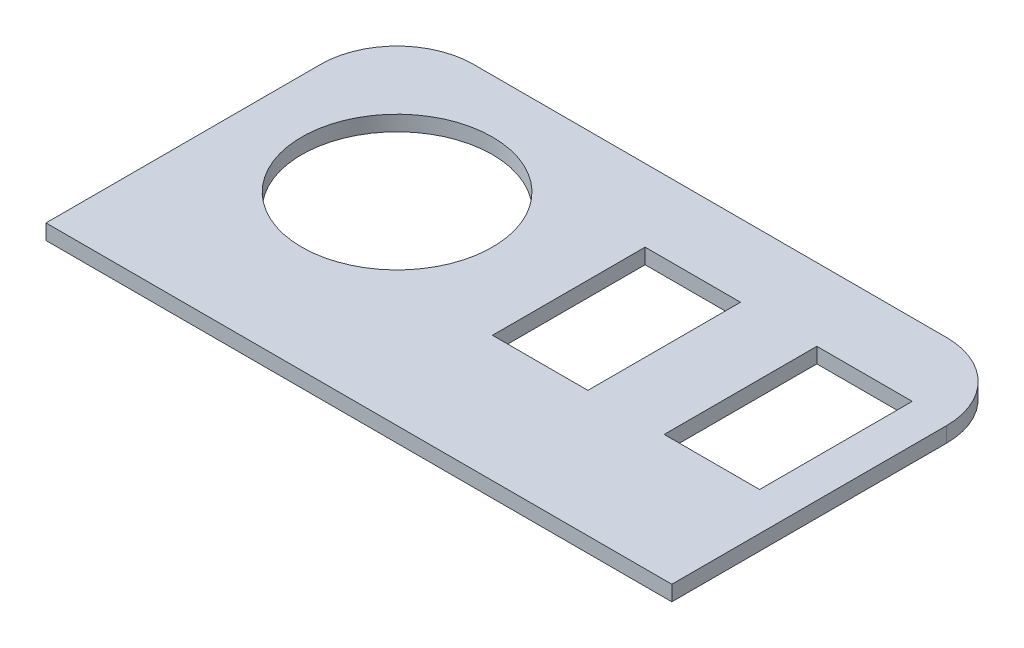
SolidWorks part; units mm, degrees
material "AISI 1020"
ref_plane "前视基准面" through (0, 0, 0) normal (0, 0, 1) x (1, 0, 0)
ref_plane "上视基准面" through (0, 0, 0) normal (0, 1, 0) x (1, 0, 0)
ref_plane "右视基准面" through (0, 0, 0) normal (1, 0, 0) x (0, 0, -1)
sketch "草图1" plane through (0, 0, 0) normal (0, 1, 0) x (1, 0, 0)
  line L1 (-41, 23) -> (41, 23)
  line L2 (-41, 23) -> (-41, -23)
  line L3 (-41, -23) -> (41, -23)
  line L4 (41, 23) -> (41, -23)
  line L5 (-41, 23) -> (41, -23) construction
  line L6 (-41, -23) -> (41, 23) construction
  line L7 (1, -6.5) -> (13.5, -6.5)
  line L8 (1, -6.5) -> (1, 13.5)
  line L9 (1, 13.5) -> (13.5, 13.5)
  line L10 (13.5, -6.5) -> (13.5, 13.5)
  line L11 (1, -6.5) -> (13.5, 13.5) construction
  line L12 (1, 13.5) -> (13.5, -6.5) construction
  line L13 (23.5, -6.5) -> (36, -6.5)
  line L14 (23.5, -6.5) -> (23.5, 13.5)
  line L15 (23.5, 13.5) -> (36, 13.5)
  line L16 (36, -6.5) -> (36, 13.5)
  line L17 (23.5, -6.5) -> (36, 13.5) construction
  line L18 (23.5, 13.5) -> (36, -6.5) construction
  circle A0 centre (-21.5, 3.5) radius 12.5
  point P0 (0, 0)
  point P8 (7.25, 3.5)
  point P13 (29.75, 3.5)
  dimension "D1" = 25
  dimension "D2" = 14
  dimension "D6" = 10
  dimension "D9" = 7
  dimension "D3" = 12.5
  dimension "D4" = 20
  dimension "D5" = 7
  dimension "D7" = 10
  dimension "D8" = 5
extrude "凸台-拉伸1" add sketch "草图1" along normal blind 2
fillet "圆角1" radius 10 2 edges at (41, 1, -23) (-41, 1, -23)
